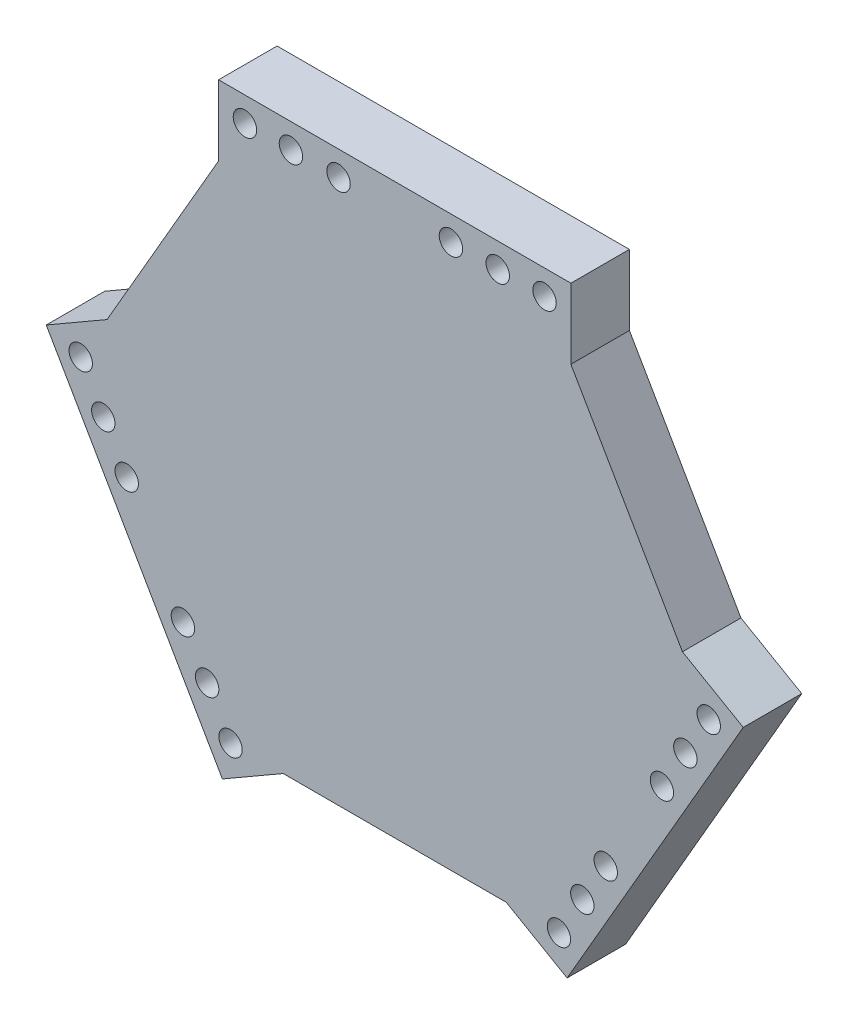
SolidWorks part; units mm, degrees
ref_plane "前基準面" through (0, 0, 0) normal (0, 0, 1) x (1, 0, 0)
ref_plane "上基準面" through (0, 0, 0) normal (0, 1, 0) x (1, 0, 0)
ref_plane "右基準面" through (0, 0, 0) normal (1, 0, 0) x (0, 0, -1)
sketch "草圖1" plane through (0, 0, 0) normal (0, 0, 1) x (1, 0, 0)
  line L0 (29.3027, 33.7186) -> (37.3027, 33.7186) construction
  line L1 (45.3027, 33.7186) -> (-5.8973, 33.7186)
  line L2 (-5.8973, 33.7186) -> (-33.9573, -14.8827)
  line L3 (-33.9573, -14.8827) -> (-5.8973, 33.7186)
  line L7 (-33.9573, -14.8827) -> (-8.3573, -59.2232)
  line L8 (-8.3573, -59.2232) -> (-33.9573, -14.8827)
  line L9 (-8.3573, -59.2232) -> (47.7627, -59.2232)
  line L10 (47.7627, -59.2232) -> (73.3627, -14.8827)
  line L11 (73.3627, -14.8827) -> (45.3027, 33.7186)
  line L12 (73.3627, -14.8827) -> (69.3627, -21.8109) construction
  line L13 (-10.3973, 37.9244) -> (49.8027, 37.9244)
  line L14 (-10.3973, 37.9244) -> (-10.3973, 25.9244)
  line L15 (-10.3973, 25.9244) -> (49.8027, 25.9244)
  line L16 (49.8027, 37.9244) -> (49.8027, 25.9244)
  line L17 (-29.4573, -7.0885) -> (0.6427, -59.2232)
  line L18 (0.6427, -59.2232) -> (-9.7496, -65.2232)
  line L19 (-9.7496, -65.2232) -> (-39.8496, -13.0885)
  line L20 (-39.8496, -13.0885) -> (-29.4573, -7.0885)
  line L21 (55.7627, -45.3668) -> (51.7627, -52.295) construction
  line L22 (68.8627, -7.0885) -> (38.7627, -59.2232)
  line L23 (38.7627, -59.2232) -> (49.155, -65.2232)
  line L24 (49.155, -65.2232) -> (79.255, -13.0885)
  line L25 (79.255, -13.0885) -> (68.8627, -7.0885)
  circle A0 centre (-5.8973, 33.7186) radius 2
  circle A1 centre (1.9623, 33.7186) radius 2
  circle A2 centre (10.1027, 33.7186) radius 2
  circle A4 centre (29.3027, 33.7186) radius 2
  circle A8 centre (-33.9573, -14.8827) radius 2
  circle A9 centre (-30.0977, -21.8109) radius 2
  circle A10 centre (-26.0977, -28.7391) radius 2
  circle A12 centre (-16.4977, -45.3668) radius 2
  circle A13 centre (-12.3573, -52.295) radius 2
  circle A14 centre (-8.3573, -59.2232) radius 2
  circle A15 centre (47.7627, -59.2232) radius 2
  circle A18 centre (55.7627, -45.3668) radius 2
  circle A22 centre (37.3027, 33.7186) radius 2
  circle A23 centre (45.3027, 33.7186) radius 2
  circle A24 centre (73.3627, -14.8827) radius 2
  circle A25 centre (69.3627, -21.8109) radius 2
  circle A26 centre (65.3627, -28.7391) radius 2
  circle A27 centre (51.7627, -52.295) radius 2
  dimension "D1" = 4
  dimension "D6" = 4
  dimension "D10" = 4
  dimension "D13" = 19.2
  dimension "D11" = 4
  dimension "D15" = 19.2
  dimension "D7" = 19.2
  dimension "D17" = 8
  dimension "D2" = 8
  dimension "D3" = 120
  dimension "D4" = 120
  dimension "D5" = 56.12
  dimension "D8" = 120
  dimension "D9" = 56.12
  dimension "D12" = 8
  dimension "D16" = 56.12
  dimension "D18" = 4.5
  dimension "D19" = 4.5
  dimension "D20" = 60.2
  dimension "D21" = 12
  dimension "D22" = 90
  dimension "D23" = 180
  dimension "D24" = 12
  dimension "D25" = 4.5
  dimension "D26" = 4.5
  dimension "D27" = 8
  dimension "D28" = 12
  dimension "D29" = 60.2
  dimension "D30" = 90
  dimension "D31" = 4.5
  dimension "D14" = 3
extrude "填料-伸長4" add sketch "草圖1" along normal blind 10 contours L22 L11 L15 L3 L17 L9 | A23 L1 A22 A4 A2 A1 A0 L3 L15 L11 | A23 L11 L16 L13 L14 L3 A0 L1 A1 A2 A4 A22 | A14 L8 A13 A12 A10 A9 A8 L2 L20 L19 L18 L9 | A14 L9 L17 L2 A8 L8 A9 A10 A12 A13 | A27 L10 A15 L9 L23 L24 L25 L11 A24 A25 A26 A18 | A27 L10 A18 A26 A25 A24 L11 L22 L9 A15
